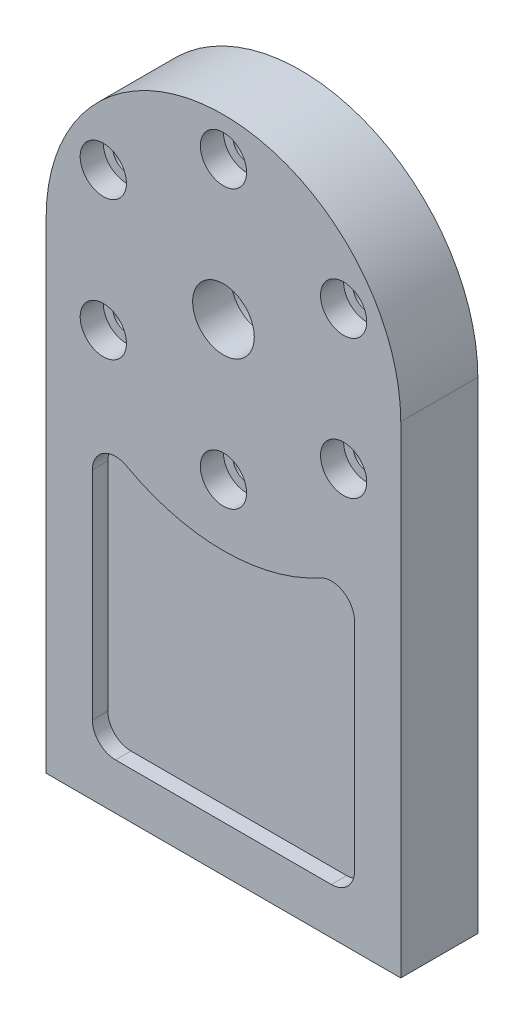
SolidWorks part; units mm, degrees
ref_plane "Front Plane" through (0, 0, 0) normal (0, 0, 1) x (1, 0, 0)
ref_plane "Top Plane" through (0, 0, 0) normal (0, 1, 0) x (1, 0, 0)
ref_plane "Right Plane" through (0, 0, 0) normal (1, 0, 0) x (0, 0, -1)
sketch "Sketch2" plane through (0, 0, 0) normal (0, 0, 1) x (1, 0, 0)
  line L0 (0, 89.4461) -> (0, -155.0469) construction
  line L1 (-46, 0) -> (46, 0)
  line L2 (-46, 0) -> (-46, -125)
  line L3 (-46, -125) -> (46, -125)
  line L4 (46, 0) -> (46, -125)
  arc A0 (46, 0) -> (-46, 0) centre (0, 0) ccw
  circle A1 centre (0, 0) radius 36 construction
  circle A2 centre (0, 36) radius 3.5
  circle A3 centre (0, 0) radius 8
  circle A4 centre (31.1769, 18) radius 3.5
  circle A5 centre (31.1769, -18) radius 3.5
  circle A6 centre (0, -36) radius 3.5
  circle A7 centre (-31.1769, -18) radius 3.5
  circle A8 centre (-31.1769, 18) radius 3.5
  point P25 (0, 0)
  dimension "D1" = 92
  dimension "D3" = 72
  dimension "D4" = 7
  dimension "D5" = 16
  dimension "D2" = 125
  dimension "D6" = 6
extrude "Boss-Extrude1" add sketch "Sketch2" along normal mid plane 20 contours A3 L1 L2 L3 L4 A7 A6 A5 | A3 L1 A0 A8 A4 A2
sketch "Sketch4" plane through (0, 0, 10) normal (0, 0, 1) x (1, 0, 0)
  circle A0 centre (0, 36) radius 6
  circle A1 centre (31.1769, 18) radius 6
  circle A2 centre (31.1769, -18) radius 6
  circle A3 centre (0, -36) radius 6
  circle A4 centre (-31.1769, -18) radius 6
  circle A5 centre (-31.1769, 18) radius 6
  point P15 (0, 0)
  dimension "D1" = 12
  dimension "D3" = 72
  dimension "D2" = 6
extrude "Cut-Extrude1" cut sketch "Sketch4" against normal blind 6
sketch "Sketch5" plane through (0, 0, 10) normal (0, 0, 1) x (1, 0, 0)
  line L6 (34, -113) -> (34, 0)
  line L7 (-34, -113) -> (34, -113)
  line L8 (-34, 0) -> (-34, -113)
  line L9 (34, -107) -> (34, -50.7937)
  line L10 (-28, -113) -> (28, -113)
  line L11 (-34, -50.7937) -> (-34, -107)
  arc A0 (-25.1034, -45.5392) -> (25.1034, -45.5392) centre (0, 0) ccw
  arc A1 (34, -107) -> (28, -113) centre (28, -107) cw
  arc A2 (-28, -113) -> (-34, -107) centre (-28, -107) cw
  arc A3 (34, -50.7937) -> (25.1034, -45.5392) centre (28, -50.7937) ccw
  arc A4 (-34, -50.7937) -> (-25.1034, -45.5392) centre (-28, -50.7937) cw
  dimension "D1" = 104
  dimension "D3" = 6
  dimension "D2" = 12
extrude "Cut-Extrude2" cut sketch "Sketch5" against normal blind 4
mirror "Mirror1" about plane through (0, 0, 0) normal (0, 0, 1) of "Cut-Extrude2"
sketch "Sketch6" plane through (0, 0, -10) normal (0, 0, -1) x (-1, 0, 0)
  circle A0 centre (0, 0) radius 12.5
  dimension "D1" = 25
extrude "Cut-Extrude3" cut sketch "Sketch6" against normal blind 10
hole_wizard "Tap Drill for M10x1.25 Tap1" positions "Sketch7" profile "Sketch8" hole size "M10x1.25" standard "ISO"
sketch "Sketch7" plane through (0, -125, 0) normal (0, -1, 0) x (-1, 0, 0)
  line L0 (-46, -10) -> (-46, 10) construction
  line L2 (46, -10) -> (-46, -10) construction
  point P0 (-30, 0)
  point P2 (30, 0)
  dimension "D1" = 60
  dimension "D2" = 16
  dimension "D3" = 10
sketch "Sketch8" plane through (30, -125, 0) normal (1, 0, 0) x (0, 0, -1)
  line L0 (0, 0) -> (0, 26.6438)
  line L1 (0, 26.6438) -> (4.4, 24)
  line L2 (4.4, 24) -> (4.4, 0)
  line L5 (4.4, 0) -> (0, 0)
  line L10 (0, 26.6438) -> (-4.4, 24) construction
  line L11 (0, -6.35) -> (0, 107.95) construction
  dimension "Hole Dia." = 8.8
  dimension "Hole Depth" = 24
  dimension "Drill Angle" = 118
